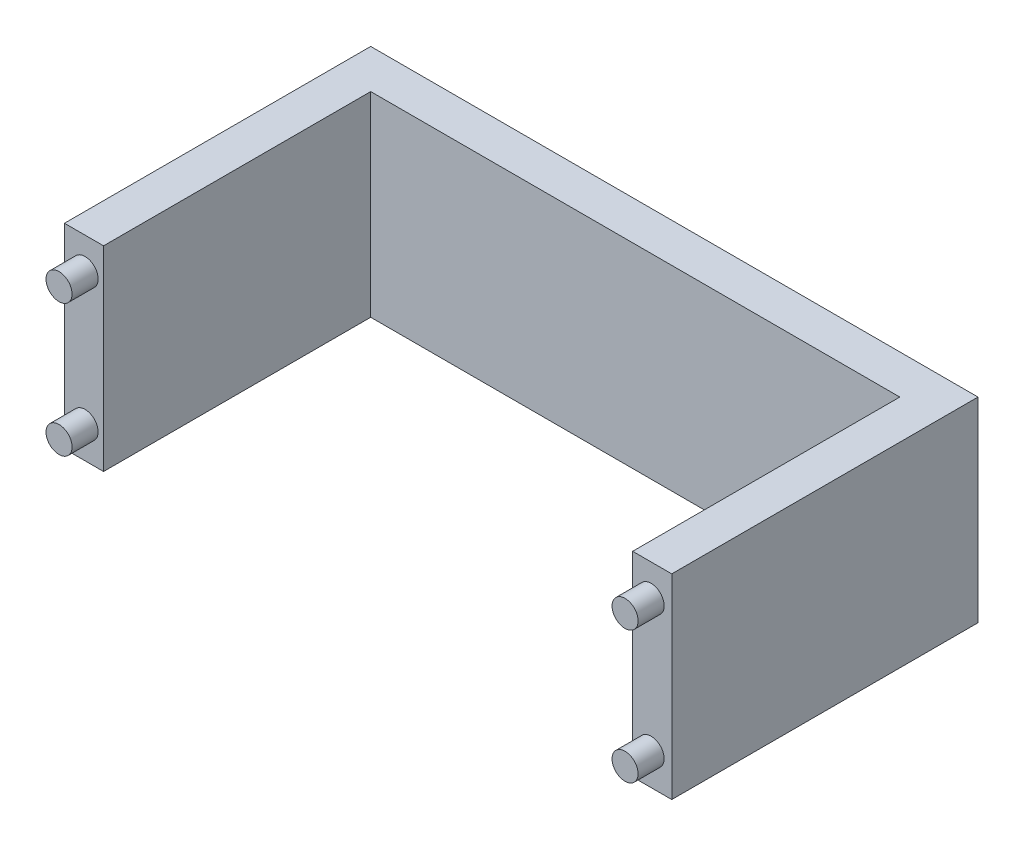
SolidWorks part; units mm, degrees
ref_plane "Front Plane" through (0, 0, 0) normal (0, 0, 1) x (1, 0, 0)
ref_plane "Top Plane" through (0, 0, 0) normal (0, 1, 0) x (1, 0, 0)
ref_plane "Right Plane" through (0, 0, 0) normal (1, 0, 0) x (0, 0, -1)
sketch "Sketch2" plane through (0, 0, 0) normal (0, 1, 0) x (1, 0, 0)
  line L0 (0, 0) -> (0, 23.5)
  line L1 (0, 23.5) -> (46.6, 23.5)
  line L2 (46.6, 23.5) -> (46.6, 0)
  line L3 (46.6, 0) -> (43.6, 0)
  line L4 (43.6, 0) -> (43.6, 20.5)
  line L5 (43.6, 20.5) -> (3, 20.5)
  line L6 (3, 20.5) -> (3, 0)
  line L7 (3, 0) -> (0, 0)
  dimension "D1" = 20.5
  dimension "D2" = 40.6
  dimension "D3" = 3
  dimension "D4" = 3
  dimension "D5" = 3
extrude "Boss-Extrude2" add sketch "Sketch2" along normal blind 15
sketch "Sketch4" plane through (0, 0, 0) normal (0, 0, 1) x (1, 0, 0)
  line L0 (3, 0) -> (3, 7.5)
  line L1 (3, 15) -> (3, 0) construction
  line L2 (3, 7.5) -> (43.6, 7.5)
  line L3 (43.6, 15) -> (43.6, 0) construction
  line L5 (1.583, 2.42) -> (45.017, 2.42)
  line L6 (1.583, 2.42) -> (1.583, 12.58)
  line L7 (1.583, 12.58) -> (45.017, 12.58)
  line L8 (45.017, 2.42) -> (45.017, 12.58)
  line L9 (1.583, 2.42) -> (45.017, 12.58) construction
  line L10 (1.583, 12.58) -> (45.017, 2.42) construction
  circle A0 centre (1.583, 2.42) radius 1
  circle A1 centre (1.583, 12.58) radius 1
  circle A2 centre (45.017, 12.58) radius 1
  circle A3 centre (45.017, 2.42) radius 1
  point P8 (23.3, 7.5)
  dimension "D1" = 2
  dimension "D2" = 2
  dimension "D3" = 2
  dimension "D4" = 2
  dimension "D5" = 10.16
  dimension "D6" = 43.434
extrude "Boss-Extrude3" add sketch "Sketch4" along normal blind 2 contours A1 | A0 | A3 | A2
